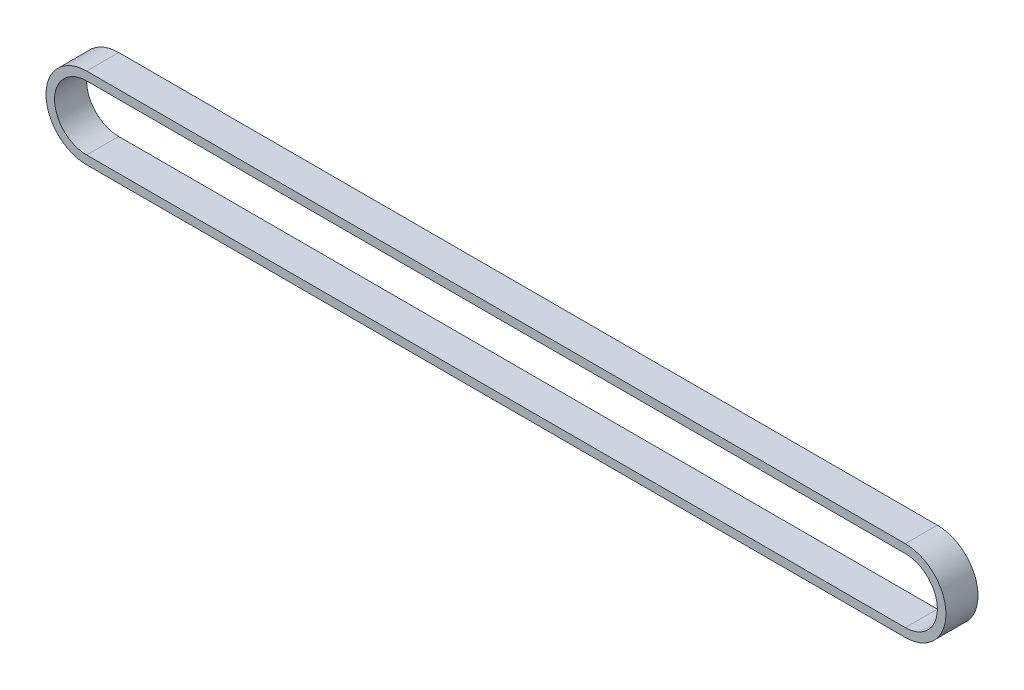
SolidWorks part; units mm, degrees
material "硅橡胶"
ref_plane "前视基准面" through (0, 0, 0) normal (0, 0, 1) x (1, 0, 0)
ref_plane "上视基准面" through (0, 0, 0) normal (0, 1, 0) x (1, 0, 0)
ref_plane "右视基准面" through (0, 0, 0) normal (1, 0, 0) x (0, 0, -1)
sketch "草图1" plane through (0, 0, 0) normal (0, 0, 1) x (1, 0, 0)
  line L0 (0, 0) -> (383, 0) construction
  line L1 (0, 15) -> (383, 15)
  line L2 (0, -15) -> (383, -15)
  line L3 (0, 19) -> (383, 19)
  line L4 (0, -19) -> (383, -19)
  arc A0 (0, 15) -> (0, -15) centre (0, 0) ccw
  arc A1 (383, -15) -> (383, 15) centre (383, 0) ccw
  arc A2 (383, -19) -> (383, 19) centre (383, 0) ccw
  arc A3 (0, 19) -> (0, -19) centre (0, 0) ccw
  point P3 (191.5, 0)
  dimension "D2" = 15
  dimension "D1" = 383
  dimension "D3" = 4
extrude "凸台-拉伸1" add sketch "草图1" along normal blind 15
